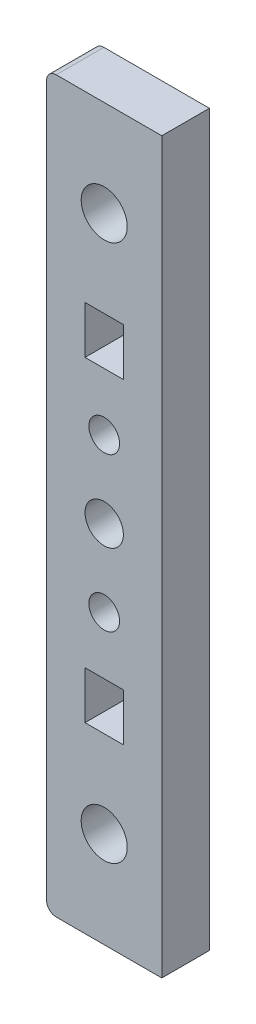
SolidWorks part; units mm, degrees
ref_plane "Front Plane" through (0, 0, 0) normal (0, 0, 1) x (1, 0, 0)
ref_plane "Top Plane" through (0, 0, 0) normal (0, 1, 0) x (1, 0, 0)
ref_plane "Right Plane" through (0, 0, 0) normal (1, 0, 0) x (0, 0, -1)
sketch "Model" plane through (0, 0, 0) normal (0, 0, 1) x (1, 0, 0)
  line L0 (-30, 185) -> (0, 185) construction
  line L1 (-27.5, 0) -> (0, 0)
  line L2 (-30, 2.5) -> (-30, 187.5)
  line L3 (-27.5, 190) -> (0, 190)
  line L4 (0, 0) -> (0, 190)
  line L5 (-30, 95) -> (0, 95) construction
  line L6 (-20, 142.4) -> (-10, 142.4)
  line L7 (-20, 142.4) -> (-20, 130)
  line L8 (-20, 130) -> (-10, 130)
  line L9 (-10, 142.4) -> (-10, 130)
  line L10 (-20, 142.4) -> (-10, 130) construction
  line L11 (-20, 130) -> (-10, 142.4) construction
  line L12 (-20, 60) -> (-10, 47.6) construction
  line L13 (-20, 47.6) -> (-10, 60) construction
  line L14 (-10, 47.6) -> (-10, 60)
  line L15 (-20, 60) -> (-10, 60)
  line L16 (-20, 47.6) -> (-20, 60)
  line L17 (-20, 47.6) -> (-10, 47.6)
  line L18 (-15, 165) -> (0, 165) construction
  line L22 (-15, 185) -> (-15, 0) construction
  circle A0 centre (-15, 165) radius 6
  circle A1 centre (-15, 95) radius 5
  arc A2 (-27.5, 190) -> (-30, 187.5) centre (-27.5, 187.5) ccw
  arc A3 (-30, 2.5) -> (-27.5, 0) centre (-27.5, 2.5) ccw
  circle A4 centre (-15, 115) radius 4
  circle A5 centre (-15, 25) radius 6
  circle A6 centre (-15, 75) radius 4
  point P18 (-15, 136.2)
  point P29 (-15, 53.8)
  dimension "D8" = 10
  dimension "D4" = 5
  dimension "D7" = 8
  dimension "D11" = 12
  dimension "D10" = 12.4
  dimension "D12" = 10
  dimension "D2" = 5
  dimension "D5" = 30
  dimension "D6" = 190
  dimension "D9" = 20
  dimension "D13" = 70
  dimension "D3" = 35
extrude "Boss-Extrude1" add sketch "Model" along normal blind 12.4
equation "\"material-thickness\"= 12.4mm"
equation "\"linear-xbar-dia\"= 8mm ' Diameter of the metal slide bar used on the X Axis"
equation "\"linear-xbar-bearingouter-dia\"= 15mm ' Diameter of the outer side of the bearing"
equation "\"linear-xthread-dia\"= 8mm ' Diameter of the metal threaded rod used on the X Axis"
equation "\"tab-width-large\"= 30mm ' Width of the large version of the Tab"
equation "\"xplate-supporttab-gapheight\"= 20mm"
equation "\"D10@Model\" = \"material-thickness\""
equation "\"D1@Boss-Extrude1\"= \"material-thickness\""
equation "\"D7@Model\"=\"linear-xbar-dia\""
equation "\"D11@Model\"=\"linear-xbar-bearingouter-dia\" - 3"
equation "\"D8@Model\"=\"linear-xthread-dia\" +2"
equation "\"D3@Model\"=\"xplate-supporttab-gapheight\" + (\"tab-width-large\"/2)"
